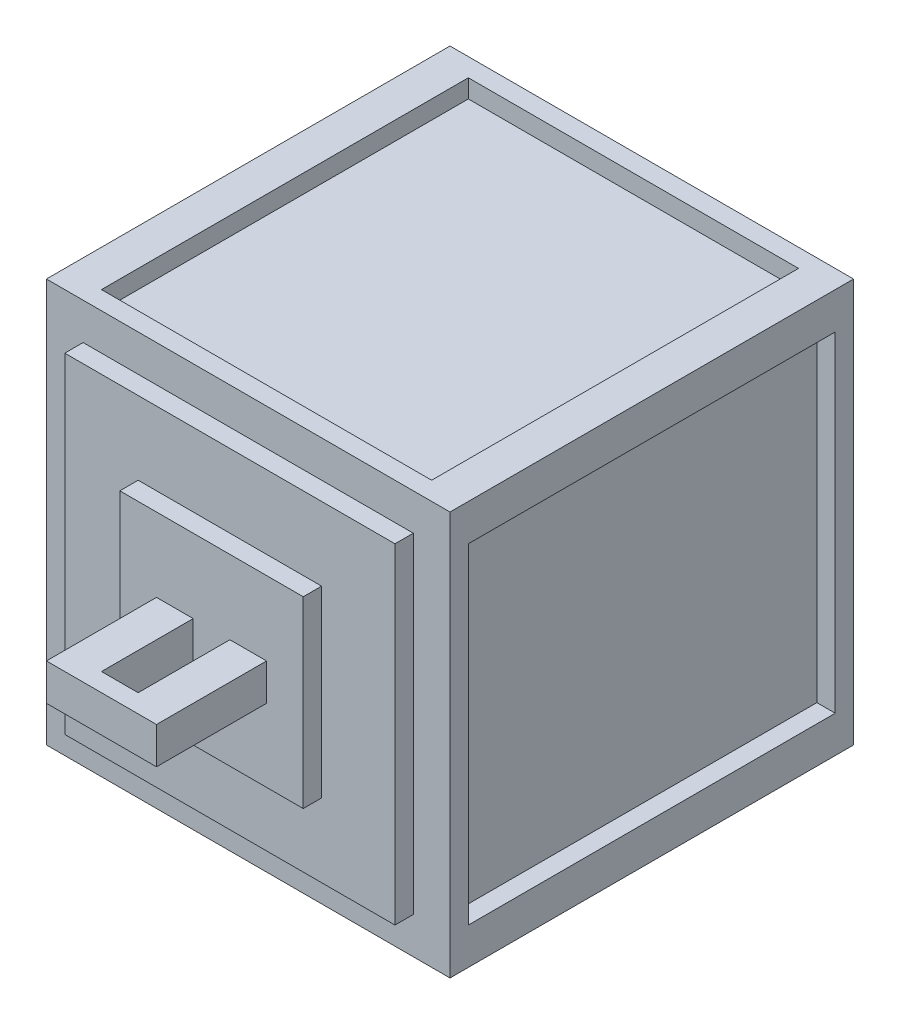
SolidWorks part; units mm, degrees
ref_plane "Alzado" through (0, 0, 0) normal (0, 0, 1) x (1, 0, 0)
ref_plane "Planta" through (0, 0, 0) normal (0, 1, 0) x (1, 0, 0)
ref_plane "Vista lateral" through (0, 0, 0) normal (1, 0, 0) x (0, 0, -1)
sketch "Croquis1" plane through (0, 0, 0) normal (0, 0, 1) x (1, 0, 0)
  line L1 (-45, 50) -> (45, 50)
  line L2 (-50, 45) -> (-50, -45)
  line L3 (-45, -50) -> (45, -50)
  line L4 (50, 45) -> (50, -45)
  line L5 (-50, 50) -> (50, -50) construction
  line L6 (-50, -50) -> (50, 50) construction
  line L7 (-50, 45) -> (-55, 45)
  line L8 (-45, 50) -> (-45, 55)
  line L9 (-45, 55) -> (-55, 55)
  line L10 (-55, 45) -> (-55, 55)
  line L11 (-45, 45) -> (-55, 55) construction
  line L12 (-45, 55) -> (-55, 45) construction
  line L13 (50, 45) -> (55, 45)
  line L14 (45, 50) -> (45, 55)
  line L15 (45, 55) -> (55, 55)
  line L16 (55, 45) -> (55, 55)
  line L17 (45, 45) -> (55, 55) construction
  line L18 (45, 55) -> (55, 45) construction
  line L19 (50, -45) -> (55, -45)
  line L20 (45, -50) -> (45, -55)
  line L21 (45, -55) -> (55, -55)
  line L22 (55, -45) -> (55, -55)
  line L23 (45, -45) -> (55, -55) construction
  line L24 (50, -50) -> (55, -45) construction
  line L25 (-50, -45) -> (-55, -45)
  line L26 (-45, -50) -> (-45, -55)
  line L27 (-45, -55) -> (-55, -55)
  line L28 (-55, -45) -> (-55, -55)
  line L29 (-45, -45) -> (-55, -55) construction
  line L30 (-45, -55) -> (-55, -45) construction
  point P0 (0, 0)
  dimension "D1" = 100
  dimension "D2" = 100
  dimension "D3" = 10
  dimension "D4" = 10
  dimension "D5" = 10
  dimension "D6" = 10
  dimension "D7" = 10
  dimension "D8" = 10
extrude "Saliente-Extruir2" add sketch "Croquis1" along normal blind 100
sketch "Croquis2" plane through (0, 0, 100) normal (0, 0, 1) x (1, 0, 0)
  line L0 (55, 55) -> (45, 55) construction
  line L1 (-55, -55) -> (55, -55)
  line L2 (-55, -55) -> (-55, 55)
  line L3 (-55, 55) -> (55, 55)
  line L4 (55, -55) -> (55, 55)
  line L5 (-55, -55) -> (55, 55) construction
  line L6 (-55, 55) -> (55, -55) construction
  line L7 (55, 45) -> (55, 55) construction
  point P0 (0, 0)
extrude "Saliente-Extruir3" add sketch "Croquis2" along normal blind 5
sketch "Croquis3" plane through (0, 0, 0) normal (0, 0, -1) x (-1, 0, 0)
  line L1 (-55, -55) -> (55, -55)
  line L2 (-55, -55) -> (-55, 55)
  line L3 (-55, 55) -> (55, 55)
  line L4 (55, -55) -> (55, 55)
  line L5 (-55, -55) -> (55, 55) construction
  line L6 (-55, 55) -> (55, -55) construction
  point P0 (0, 0)
extrude "Saliente-Extruir4" add sketch "Croquis3" along normal blind 5
sketch "Croquis4" plane through (0, 0, 105) normal (0, 0, 1) x (1, 0, 0)
  line L1 (-45, -45) -> (45, -45)
  line L2 (-45, -45) -> (-45, 45)
  line L3 (-45, 45) -> (45, 45)
  line L4 (45, -45) -> (45, 45)
  line L5 (-45, -45) -> (45, 45) construction
  line L6 (-45, 45) -> (45, -45) construction
  point P0 (0, 0)
  dimension "D1" = 90
  dimension "D2" = 90
extrude "Saliente-Extruir5" add sketch "Croquis4" along normal blind 5
sketch "Croquis5" plane through (0, 0, 110) normal (0, 0, 1) x (1, 0, 0)
  line L1 (-25, -25) -> (25, -25)
  line L2 (-25, -25) -> (-25, 25)
  line L3 (-25, 25) -> (25, 25)
  line L4 (25, -25) -> (25, 25)
  line L5 (-25, -25) -> (25, 25) construction
  line L6 (-25, 25) -> (25, -25) construction
  point P0 (0, 0)
  dimension "D1" = 50
  dimension "D2" = 50
extrude "Saliente-Extruir6" add sketch "Croquis5" along normal blind 5
sketch "Croquis6" plane through (0, 0, 115) normal (0, 0, 1) x (1, 0, 0)
  line L0 (0, 0) -> (0, 10.0508) construction
  line L1 (-15, -5.1554) -> (-5, -5.1554)
  line L2 (-15, -5.1554) -> (-15, 4.8446)
  line L3 (-15, 4.8446) -> (-5, 4.8446)
  line L4 (-5, -5.1554) -> (-5, 4.8446)
  line L5 (-15, -5.1554) -> (-5, 4.8446) construction
  line L6 (-15, 4.8446) -> (-5, -5.1554) construction
  line L7 (15, 4.8446) -> (5, 4.8446)
  line L8 (5, -5.1554) -> (5, 4.8446)
  line L9 (15, -5.1554) -> (5, -5.1554)
  line L10 (15, -5.1554) -> (15, 4.8446)
  point P0 (-10, -0.1554)
  dimension "D1" = 10
  dimension "D2" = 10
  dimension "D3" = 10
extrude "Saliente-Extruir7" add sketch "Croquis6" along normal blind 25
sketch "Croquis7" plane through (0, 0, 140) normal (0, 0, 1) x (1, 0, 0)
  line L1 (-15, 4.8446) -> (15, 4.8446)
  line L2 (-15, 4.8446) -> (-15, -5.1554)
  line L3 (-15, -5.1554) -> (15, -5.1554)
  line L4 (15, 4.8446) -> (15, -5.1554)
extrude "Saliente-Extruir8" add sketch "Croquis7" along normal blind 5
